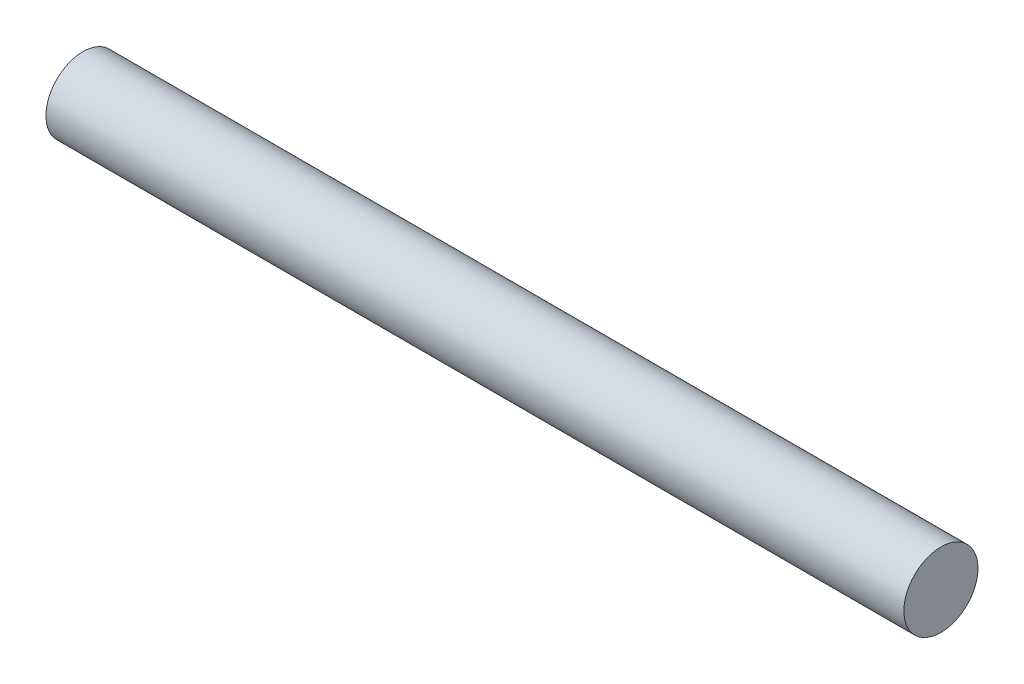
SolidWorks part; units mm, degrees
material "6061 Alloy"
ref_plane "Front Plane" through (0, 0, 0) normal (0, 0, 1) x (1, 0, 0)
ref_plane "Top Plane" through (0, 0, 0) normal (0, 1, 0) x (1, 0, 0)
ref_plane "Right Plane" through (0, 0, 0) normal (1, 0, 0) x (0, 0, -1)
sketch "Sketch1" plane through (0, 0, 0) normal (1, 0, 0) x (0, 0, -1)
  circle A0 centre (0, 0) radius 3
  dimension "D1" = 6
extrude "Boss-Extrude1" add sketch "Sketch1" along normal blind 69.42
